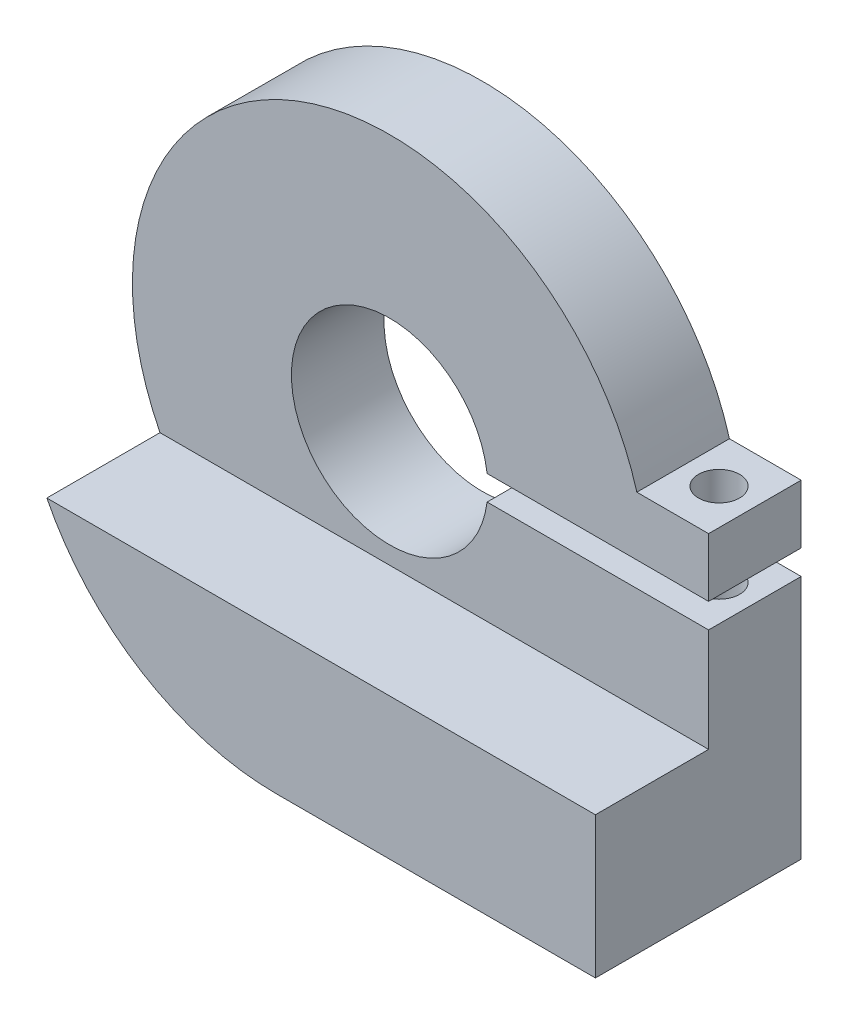
SolidWorks part; units mm, degrees
ref_plane "Front Plane" through (0, 0, 0) normal (0, 0, 1) x (1, 0, 0)
ref_plane "Top Plane" through (0, 0, 0) normal (0, 1, 0) x (1, 0, 0)
ref_plane "Right Plane" through (0, 0, 0) normal (1, 0, 0) x (0, 0, -1)
sketch "Sketch1" plane through (0, 0, 0) normal (0, 0, 1) x (1, 0, 0)
  line L1 (0, -12.5) -> (15.5, -12.5)
  line L4 (15.5, -12.5) -> (15.5, -0.6)
  line L6 (15.5, 0.6) -> (15.5, 3.4525)
  line L7 (15.5, 3.4525) -> (12.0138, 3.4525)
  line L8 (15.5, 0.6) -> (4.736, 0.6)
  line L10 (15.5, -0.6) -> (4.736, -0.6)
  arc A0 (12.0138, 3.4525) -> (0, -12.5) centre (0, 0) ccw
  arc A2 (4.736, 0.6) -> (4.736, -0.6) centre (0, 0) ccw
  dimension "D1" = 25
  dimension "D2" = 11.9
  dimension "D3" = 15.5
extrude "Boss-Extrude1" add sketch "Sketch1" along normal blind 4.5 contours A2 L10 L4 L1 A0 L7 L6 L8
sketch "Sketch2" plane through (0, 0, 4.5) normal (0, 0, 1) x (1, 0, 0)
  line L5 (15.5, -12.5) -> (0, -12.5)
  line L6 (15.5, -12.5) -> (15.5, -5.6288)
  line L7 (15.5, -5.6288) -> (-11.161, -5.6288)
  arc A0 (-11.161, -5.6288) -> (0, -12.5) centre (0, 0) ccw
extrude "Boss-Extrude2" add sketch "Sketch2" along normal blind 5.5 contours L7 A0 L5 L6
sketch "Sketch4" plane through (0, 3.4525, 0) normal (0, 1, 0) x (1, 0, 0)
  line L0 (15.5, -2.25) -> (12.0138, -2.25) construction
  line L1 (15.5, -4.5) -> (15.5, 0) construction
  line L2 (12.0138, -4.5) -> (12.0138, 0) construction
  circle A0 centre (13.7569, -2.25) radius 1
extrude "Cut-Extrude1" cut sketch "Sketch4" against normal blind 5.5
